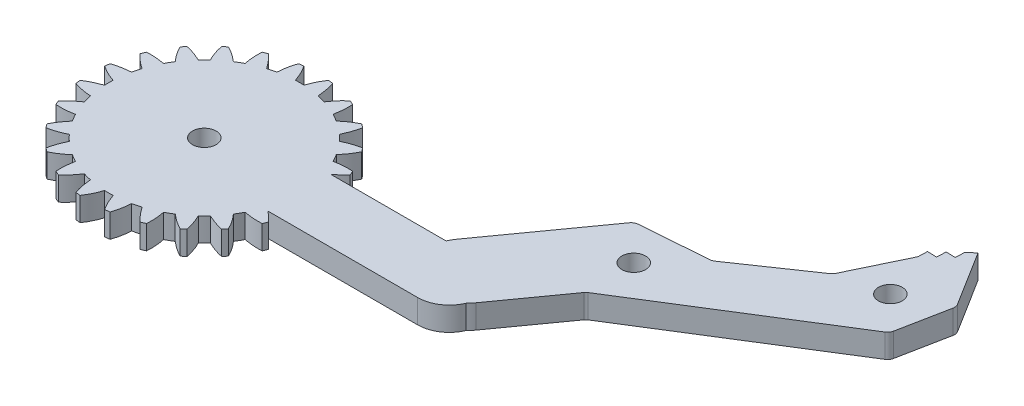
SolidWorks part; units mm, degrees
ref_plane "Front Plane" through (0, 0, 0) normal (0, 0, 1) x (1, 0, 0)
ref_plane "Top Plane" through (0, 0, 0) normal (0, 1, 0) x (1, 0, 0)
ref_plane "Right Plane" through (0, 0, 0) normal (1, 0, 0) x (0, 0, -1)
sketch "Sketch2" plane through (0, 0, 0) normal (0, 1, 0) x (1, 0, 0)
  line L0 (31, 4) -> (12.0129, 4)
  line L1 (31, -4) -> (12.0325, -4)
  line L2 (0, 0) -> (0, 12.09) construction
  line L3 (0, 0) -> (4.397, 16.4099) construction
  line L4 (0, 0) -> (-3.1291, 11.678) construction
  line L5 (-3.6882, 13.7644) -> (-4.4272, 16.5225) construction
  line L6 (0, 14.25) -> (0, 16.5009) construction
  line L7 (0, 0) -> (4.629, 11.1754) construction
  line L8 (4.629, 11.1754) -> (5.4532, 13.1653) construction
  circle A2 centre (31, 0) radius 1.5
  arc A3 (31, -4) -> (31, 4) centre (31, 0) ccw
  arc A12 (6.045, 10.4702) -> (5.5713, 10.7298) centre (0, 0) ccw
  arc A13 (3.6475, 11.5267) -> (3.1291, 11.678) centre (0, 0) ccw
  arc A81 (6.5065, 10.1899) -> (6.045, 10.4702) centre (0, 0) ccw
  arc A82 (8.5489, 8.5489) -> (8.1586, 8.9222) centre (0, 0) ccw
  circle A85 centre (0, 0) radius 1.5
  arc A87 (8.9148, 11.117) -> (8.4309, 11.4884) centre (0, 0) ccw
  arc A89 (8.9221, 8.1587) -> (8.5489, 8.5489) centre (0, 0) ccw
  arc A95 (10.4702, 6.045) -> (10.1898, 6.5066) centre (0, 0) ccw
  arc A97 (11.4884, 8.4309) -> (11.117, 8.9148) centre (0, 0) ccw
  arc A98 (10.7297, 5.5714) -> (10.4702, 6.045) centre (0, 0) ccw
  arc A100 (13.279, 5.1702) -> (13.0455, 5.7338) centre (0, 0) ccw
  arc A115 (10.4702, -6.045) -> (10.7298, -5.5713) centre (0, 0) ccw
  arc A117 (13.0455, -5.7338) -> (13.279, -5.1702) centre (0, 0) ccw
  arc A121 (5.7338, 13.0455) -> (5.1702, 13.279) centre (0, 0) ccw
  arc A161 (10.1899, -6.5065) -> (10.4702, -6.045) centre (0, 0) ccw
  arc A162 (8.5489, -8.5489) -> (8.9222, -8.1586) centre (0, 0) ccw
  arc A163 (11.117, -8.9148) -> (11.4884, -8.4309) centre (0, 0) ccw
  arc A164 (8.1587, -8.9221) -> (8.5489, -8.5489) centre (0, 0) ccw
  arc A165 (6.045, -10.4702) -> (6.5066, -10.1898) centre (0, 0) ccw
  arc A166 (8.4309, -11.4884) -> (8.9148, -11.117) centre (0, 0) ccw
  arc A167 (5.5714, -10.7297) -> (6.045, -10.4702) centre (0, 0) ccw
  arc A168 (3.1291, -11.678) -> (3.6476, -11.5266) centre (0, 0) ccw
  arc A169 (5.1702, -13.279) -> (5.7338, -13.0455) centre (0, 0) ccw
  arc A170 (2.6045, -11.8061) -> (3.1291, -11.678) centre (0, 0) ccw
  arc A171 (0, -12.09) -> (0.54, -12.0779) centre (0, 0) ccw
  arc A172 (1.5572, -14.1647) -> (2.162, -14.085) centre (0, 0) ccw
  arc A173 (-0.5399, -12.0779) -> (0, -12.09) centre (0, 0) ccw
  arc A174 (-3.1291, -11.678) -> (-2.6044, -11.8062) centre (0, 0) ccw
  arc A175 (-2.162, -14.085) -> (-1.5572, -14.1647) centre (0, 0) ccw
  arc A176 (-3.6475, -11.5267) -> (-3.1291, -11.678) centre (0, 0) ccw
  arc A177 (-6.045, -10.4702) -> (-5.5713, -10.7298) centre (0, 0) ccw
  arc A178 (-5.7338, -13.0455) -> (-5.1702, -13.279) centre (0, 0) ccw
  arc A179 (-6.5065, -10.1899) -> (-6.045, -10.4702) centre (0, 0) ccw
  arc A180 (-8.5489, -8.5489) -> (-8.1586, -8.9222) centre (0, 0) ccw
  arc A181 (-8.9148, -11.117) -> (-8.4309, -11.4884) centre (0, 0) ccw
  arc A182 (-8.9221, -8.1587) -> (-8.5489, -8.5489) centre (0, 0) ccw
  arc A183 (-10.4702, -6.045) -> (-10.1898, -6.5066) centre (0, 0) ccw
  arc A184 (-11.4884, -8.4309) -> (-11.117, -8.9148) centre (0, 0) ccw
  arc A185 (-10.7297, -5.5714) -> (-10.4702, -6.045) centre (0, 0) ccw
  arc A186 (-11.678, -3.1291) -> (-11.5266, -3.6476) centre (0, 0) ccw
  arc A187 (-13.279, -5.1702) -> (-13.0455, -5.7338) centre (0, 0) ccw
  arc A188 (-11.8061, -2.6045) -> (-11.678, -3.1291) centre (0, 0) ccw
  arc A189 (-12.09, 0) -> (-12.0779, -0.54) centre (0, 0) ccw
  arc A190 (-14.1647, -1.5572) -> (-14.085, -2.162) centre (0, 0) ccw
  arc A191 (-12.0779, 0.5399) -> (-12.09, 0) centre (0, 0) ccw
  arc A192 (-11.678, 3.1291) -> (-11.8062, 2.6044) centre (0, 0) ccw
  arc A193 (-14.085, 2.162) -> (-14.1647, 1.5572) centre (0, 0) ccw
  arc A194 (-11.5267, 3.6475) -> (-11.678, 3.1291) centre (0, 0) ccw
  arc A195 (-10.4702, 6.045) -> (-10.7298, 5.5713) centre (0, 0) ccw
  arc A196 (-13.0455, 5.7338) -> (-13.279, 5.1702) centre (0, 0) ccw
  arc A197 (-10.1899, 6.5065) -> (-10.4702, 6.045) centre (0, 0) ccw
  arc A198 (-8.5489, 8.5489) -> (-8.9222, 8.1586) centre (0, 0) ccw
  arc A199 (-11.117, 8.9148) -> (-11.4884, 8.4309) centre (0, 0) ccw
  arc A200 (-8.1587, 8.9221) -> (-8.5489, 8.5489) centre (0, 0) ccw
  arc A201 (-6.045, 10.4702) -> (-6.5066, 10.1898) centre (0, 0) ccw
  arc A202 (-8.4309, 11.4884) -> (-8.9148, 11.117) centre (0, 0) ccw
  arc A203 (-5.5714, 10.7297) -> (-6.045, 10.4702) centre (0, 0) ccw
  arc A204 (-3.1291, 11.678) -> (-3.6476, 11.5266) centre (0, 0) ccw
  arc A205 (-5.1702, 13.279) -> (-5.7338, 13.0455) centre (0, 0) ccw
  arc A206 (-2.6045, 11.8061) -> (-3.1291, 11.678) centre (0, 0) ccw
  arc A207 (0, 12.09) -> (-0.54, 12.0779) centre (0, 0) ccw
  arc A208 (-1.5572, 14.1647) -> (-2.162, 14.085) centre (0, 0) ccw
  arc A209 (0.5399, 12.0779) -> (0, 12.09) centre (0, 0) ccw
  arc A210 (3.1291, 11.678) -> (2.6044, 11.8062) centre (0, 0) ccw
  arc A211 (2.162, 14.085) -> (1.5572, 14.1647) centre (0, 0) ccw
  arc A212 (12.09, 0) -> (12.0779, 0.54) centre (0, 0) ccw [skipped]
  arc A213 (14.1647, 1.5572) -> (14.085, 2.162) centre (0, 0) ccw [skipped]
  arc A214 (12.0779, -0.5399) -> (12.09, 0) centre (0, 0) ccw [skipped]
  arc A215 (11.678, -3.1291) -> (11.8062, -2.6044) centre (0, 0) ccw [skipped]
  arc A216 (14.085, -2.162) -> (14.1647, -1.5572) centre (0, 0) ccw [skipped]
  arc A217 (11.5267, -3.6475) -> (11.678, -3.1291) centre (0, 0) ccw [skipped]
  arc A218 (11.8061, 2.6045) -> (11.678, 3.1291) centre (0, 0) ccw [skipped]
  arc A219 (11.678, 3.1291) -> (11.5266, 3.6476) centre (0, 0) ccw [skipped]
  spline S0 degree 3 poles (8.9148, 11.117) (8.7604, 10.3435) (8.4826, 9.6001) (8.1586, 8.9222) knots 0.154713 0.154713 0.154713 0.154713 1 1 1 1
  spline S1 degree 3 poles (6.5065, 10.1899) (7.0658, 10.6979) (7.7126, 11.1471) (8.4309, 11.4884) knots 0 0 0 0 0.845227 0.845227 0.845227 0.845227
  spline S2 degree 3 poles (11.4884, 8.4309) (11.139, 7.7237) (10.6783, 7.0775) (10.1898, 6.5066) knots 0.154713 0.154713 0.154713 0.154713 1 1 1 1
  spline S3 degree 3 poles (8.9221, 8.1587) (9.5939, 8.5047) (10.3348, 8.7711) (11.117, 8.9148) knots 0 0 0 0 0.845227 0.845227 0.845227 0.845227
  spline S4 degree 3 poles (3.6475, 11.5267) (4.0562, 12.1622) (4.5647, 12.7634) (5.1702, 13.279) knots 0 0 0 0 0.845227 0.845227 0.845227 0.845227
  spline S5 degree 3 poles (5.7338, 13.0455) (5.7848, 12.2584) (5.7089, 11.4685) (5.5713, 10.7298) knots 0.154713 0.154713 0.154713 0.154713 1 1 1 1
  spline S6 degree 3 poles (13.279, 5.1702) (12.8955, 4.7335) (12.4622, 4.3445) (12.0129, 4) knots 0.154713 0.154713 0.154713 0.154713 0.77749 0.77749 0.77749 0.77749
  spline S7 degree 3 poles (10.7297, 5.5714) (11.4681, 5.7318) (12.2528, 5.7974) (13.0455, 5.7338) knots 0 0 0 0 0.845227 0.845227 0.845227 0.845227
  spline S12 degree 3 poles (13.0455, -5.7338) (12.2584, -5.7848) (11.4685, -5.7089) (10.7298, -5.5713) knots 0.154713 0.154713 0.154713 0.154713 1 1 1 1
  spline S13 degree 3 poles (12.0325, -4) (12.4803, -4.3376) (12.9025, -4.728) (13.279, -5.1702) knots 0.228019 0.228019 0.228019 0.228019 0.845227 0.845227 0.845227 0.845227
  spline S14 degree 3 poles (11.117, -8.9148) (10.3435, -8.7604) (9.6001, -8.4826) (8.9222, -8.1586) knots 0.154713 0.154713 0.154713 0.154713 1 1 1 1
  spline S15 degree 3 poles (10.1899, -6.5065) (10.6979, -7.0658) (11.1471, -7.7126) (11.4884, -8.4309) knots 0 0 0 0 0.845227 0.845227 0.845227 0.845227
  spline S16 degree 3 poles (8.4309, -11.4884) (7.7237, -11.139) (7.0775, -10.6783) (6.5066, -10.1898) knots 0.154713 0.154713 0.154713 0.154713 1 1 1 1
  spline S17 degree 3 poles (8.1587, -8.9221) (8.5047, -9.5939) (8.7711, -10.3348) (8.9148, -11.117) knots 0 0 0 0 0.845227 0.845227 0.845227 0.845227
  spline S18 degree 3 poles (5.1702, -13.279) (4.5775, -12.7584) (4.0726, -12.1462) (3.6476, -11.5266) knots 0.154713 0.154713 0.154713 0.154713 1 1 1 1
  spline S19 degree 3 poles (5.5714, -10.7297) (5.7318, -11.4681) (5.7974, -12.2528) (5.7338, -13.0455) knots 0 0 0 0 0.845227 0.845227 0.845227 0.845227
  spline S20 degree 3 poles (1.5572, -14.1647) (1.1194, -13.5085) (0.7902, -12.7864) (0.54, -12.0779) knots 0.154713 0.154713 0.154713 0.154713 1 1 1 1
  spline S21 degree 3 poles (2.6045, -11.8061) (2.5683, -12.5609) (2.4286, -13.3358) (2.162, -14.085) knots 0 0 0 0 0.845227 0.845227 0.845227 0.845227
  spline S22 degree 3 poles (-2.162, -14.085) (-2.415, -13.3379) (-2.5461, -12.5553) (-2.6044, -11.8062) knots 0.154713 0.154713 0.154713 0.154713 1 1 1 1
  spline S23 degree 3 poles (-0.5399, -12.0779) (-0.7702, -12.7976) (-1.1057, -13.5099) (-1.5572, -14.1647) knots 0 0 0 0 0.845227 0.845227 0.845227 0.845227
  spline S24 degree 3 poles (-5.7338, -13.0455) (-5.7848, -12.2584) (-5.7089, -11.4685) (-5.5713, -10.7298) knots 0.154713 0.154713 0.154713 0.154713 1 1 1 1
  spline S25 degree 3 poles (-3.6475, -11.5267) (-4.0562, -12.1622) (-4.5647, -12.7634) (-5.1702, -13.279) knots 0 0 0 0 0.845227 0.845227 0.845227 0.845227
  spline S26 degree 3 poles (-8.9148, -11.117) (-8.7604, -10.3435) (-8.4826, -9.6001) (-8.1586, -8.9222) knots 0.154713 0.154713 0.154713 0.154713 1 1 1 1
  spline S27 degree 3 poles (-6.5065, -10.1899) (-7.0658, -10.6979) (-7.7126, -11.1471) (-8.4309, -11.4884) knots 0 0 0 0 0.845227 0.845227 0.845227 0.845227
  spline S28 degree 3 poles (-11.4884, -8.4309) (-11.139, -7.7237) (-10.6783, -7.0775) (-10.1898, -6.5066) knots 0.154713 0.154713 0.154713 0.154713 1 1 1 1
  spline S29 degree 3 poles (-8.9221, -8.1587) (-9.5939, -8.5047) (-10.3348, -8.7711) (-11.117, -8.9148) knots 0 0 0 0 0.845227 0.845227 0.845227 0.845227
  spline S30 degree 3 poles (-13.279, -5.1702) (-12.7584, -4.5775) (-12.1462, -4.0726) (-11.5266, -3.6476) knots 0.154713 0.154713 0.154713 0.154713 1 1 1 1
  spline S31 degree 3 poles (-10.7297, -5.5714) (-11.4681, -5.7318) (-12.2528, -5.7974) (-13.0455, -5.7338) knots 0 0 0 0 0.845227 0.845227 0.845227 0.845227
  spline S32 degree 3 poles (-14.1647, -1.5572) (-13.5085, -1.1194) (-12.7864, -0.7902) (-12.0779, -0.54) knots 0.154713 0.154713 0.154713 0.154713 1 1 1 1
  spline S33 degree 3 poles (-11.8061, -2.6045) (-12.5609, -2.5683) (-13.3358, -2.4286) (-14.085, -2.162) knots 0 0 0 0 0.845227 0.845227 0.845227 0.845227
  spline S34 degree 3 poles (-14.085, 2.162) (-13.3379, 2.415) (-12.5553, 2.5461) (-11.8062, 2.6044) knots 0.154713 0.154713 0.154713 0.154713 1 1 1 1
  spline S35 degree 3 poles (-12.0779, 0.5399) (-12.7976, 0.7702) (-13.5099, 1.1057) (-14.1647, 1.5572) knots 0 0 0 0 0.845227 0.845227 0.845227 0.845227
  spline S36 degree 3 poles (-13.0455, 5.7338) (-12.2584, 5.7848) (-11.4685, 5.7089) (-10.7298, 5.5713) knots 0.154713 0.154713 0.154713 0.154713 1 1 1 1
  spline S37 degree 3 poles (-11.5267, 3.6475) (-12.1622, 4.0562) (-12.7634, 4.5647) (-13.279, 5.1702) knots 0 0 0 0 0.845227 0.845227 0.845227 0.845227
  spline S38 degree 3 poles (-11.117, 8.9148) (-10.3435, 8.7604) (-9.6001, 8.4826) (-8.9222, 8.1586) knots 0.154713 0.154713 0.154713 0.154713 1 1 1 1
  spline S39 degree 3 poles (-10.1899, 6.5065) (-10.6979, 7.0658) (-11.1471, 7.7126) (-11.4884, 8.4309) knots 0 0 0 0 0.845227 0.845227 0.845227 0.845227
  spline S40 degree 3 poles (-8.4309, 11.4884) (-7.7237, 11.139) (-7.0775, 10.6783) (-6.5066, 10.1898) knots 0.154713 0.154713 0.154713 0.154713 1 1 1 1
  spline S41 degree 3 poles (-8.1587, 8.9221) (-8.5047, 9.5939) (-8.7711, 10.3348) (-8.9148, 11.117) knots 0 0 0 0 0.845227 0.845227 0.845227 0.845227
  spline S42 degree 3 poles (-5.1702, 13.279) (-4.5775, 12.7584) (-4.0726, 12.1462) (-3.6476, 11.5266) knots 0.154713 0.154713 0.154713 0.154713 1 1 1 1
  spline S43 degree 3 poles (-5.5714, 10.7297) (-5.7318, 11.4681) (-5.7974, 12.2528) (-5.7338, 13.0455) knots 0 0 0 0 0.845227 0.845227 0.845227 0.845227
  spline S44 degree 3 poles (-1.5572, 14.1647) (-1.1194, 13.5085) (-0.7902, 12.7864) (-0.54, 12.0779) knots 0.154713 0.154713 0.154713 0.154713 1 1 1 1
  spline S45 degree 3 poles (-2.6045, 11.8061) (-2.5683, 12.5609) (-2.4286, 13.3358) (-2.162, 14.085) knots 0 0 0 0 0.845227 0.845227 0.845227 0.845227
  spline S46 degree 3 poles (2.162, 14.085) (2.415, 13.3379) (2.5461, 12.5553) (2.6044, 11.8062) knots 0.154713 0.154713 0.154713 0.154713 1 1 1 1
  spline S47 degree 3 poles (0.5399, 12.0779) (0.7702, 12.7976) (1.1057, 13.5099) (1.5572, 14.1647) knots 0 0 0 0 0.845227 0.845227 0.845227 0.845227
  point P11 (0, 12.09)
  point P15 (-3.1291, 11.678)
  point P167 (0, 0)
  point P177 (0, 0)
  dimension "D1" = 3
  dimension "D2" = 8
  dimension "D7" = 24
  dimension "D8" = 3.1561
  dimension "D6" = 24
  dimension "D15" = 0.61
  dimension "D3" = 31
  dimension "D4" = 15
  dimension "D5" = 15
  dimension "D16" = 7.5
  dimension "D17" = 180
extrude "Boss-Extrude1" add sketch "Sketch2" along normal blind 3
sketch "Sketch3" plane through (0, 3, 0) normal (0, 1, 0) x (1, 0, 0)
  line L14 (45.3426, 18.6333) -> (36.9248, 17.9912)
  line L15 (36.1879, 17.5766) -> (27.1233, 4.925)
  line L16 (35.2521, -0.8992) -> (40.9613, 7.0691)
  line L17 (41.2438, 7.3344) -> (64.3402, 21.7828)
  line L18 (64.791, 22.4375) -> (66.023, 28.6988)
  line L19 (65.8895, 29.4222) -> (61.5649, 36.3354)
  line L20 (61.5649, 36.3354) -> (60.6639, 35.5734)
  line L21 (60.6639, 35.5734) -> (60.6203, 34.3942)
  line L22 (60.6203, 34.3942) -> (59.4411, 34.4378)
  line L23 (59.4411, 34.4378) -> (59.3976, 33.2586)
  line L24 (59.3976, 33.2586) -> (58.2184, 33.3021)
  line L25 (58.2184, 33.3021) -> (58.1748, 32.1229)
  line L26 (58.1748, 32.1229) -> (54.8061, 25.1039)
  line L27 (54.469, 24.7111) -> (45.831, 18.8049)
  line L28 (45.3426, 18.6333) -> (36.9248, 17.9912)
  line L29 (36.1879, 17.5766) -> (27.1233, 4.925)
  line L30 (35.2521, -0.8992) -> (40.9613, 7.0691)
  line L31 (41.2438, 7.3344) -> (64.3402, 21.7828)
  line L32 (64.791, 22.4375) -> (66.023, 28.6988)
  line L33 (65.8895, 29.4222) -> (61.5649, 36.3354)
  line L34 (61.5649, 36.3354) -> (60.6639, 35.5734)
  line L35 (60.6639, 35.5734) -> (60.6203, 34.3942)
  line L36 (60.6203, 34.3942) -> (59.4411, 34.4378)
  line L37 (59.4411, 34.4378) -> (59.3976, 33.2586)
  line L38 (59.3976, 33.2586) -> (58.2184, 33.3021)
  line L39 (58.2184, 33.3021) -> (58.1748, 32.1229)
  line L40 (58.1748, 32.1229) -> (54.8061, 25.1039)
  line L41 (54.469, 24.7111) -> (45.831, 18.8049)
  circle A1 centre (40.8595, 13.4783) radius 1.5
  circle A2 centre (40.8595, 13.4783) radius 1.5
  circle A3 centre (60.5239, 26.283) radius 1.5
  circle A4 centre (60.5239, 26.283) radius 1.5
  arc A7 (45.3426, 18.6333) -> (45.831, 18.8049) centre (45.2666, 19.6304) ccw
  arc A8 (36.9248, 17.9912) -> (36.1879, 17.5766) centre (37.0008, 16.9941) ccw
  arc A9 (27.1233, 4.925) -> (35.2521, -0.8992) centre (31.1877, 2.0129) ccw
  arc A10 (41.2438, 7.3344) -> (40.9613, 7.0691) centre (41.7742, 6.4867) ccw
  arc A11 (64.3402, 21.7828) -> (64.791, 22.4375) centre (63.8098, 22.6306) ccw
  arc A12 (66.023, 28.6988) -> (65.8895, 29.4222) centre (65.0418, 28.8918) ccw
  arc A13 (54.469, 24.7111) -> (54.8061, 25.1039) centre (53.9046, 25.5366) ccw
  arc A14 (45.3426, 18.6333) -> (45.831, 18.8049) centre (45.2666, 19.6304) ccw
  arc A15 (36.9248, 17.9912) -> (36.1879, 17.5766) centre (37.0008, 16.9941) ccw
  arc A16 (27.1233, 4.925) -> (35.2521, -0.8992) centre (31.1877, 2.0129) ccw
  arc A17 (41.2438, 7.3344) -> (40.9613, 7.0691) centre (41.7742, 6.4867) ccw
  arc A18 (64.3402, 21.7828) -> (64.791, 22.4375) centre (63.8098, 22.6306) ccw
  arc A19 (66.023, 28.6988) -> (65.8895, 29.4222) centre (65.0418, 28.8918) ccw
  arc A20 (54.469, 24.7111) -> (54.8061, 25.1039) centre (53.9046, 25.5366) ccw
  dimension "D1" = 0
  dimension "D2" = 0
  dimension "D3" = 0
extrude "Boss-Extrude2" add sketch "Sketch3" against normal blind 3
